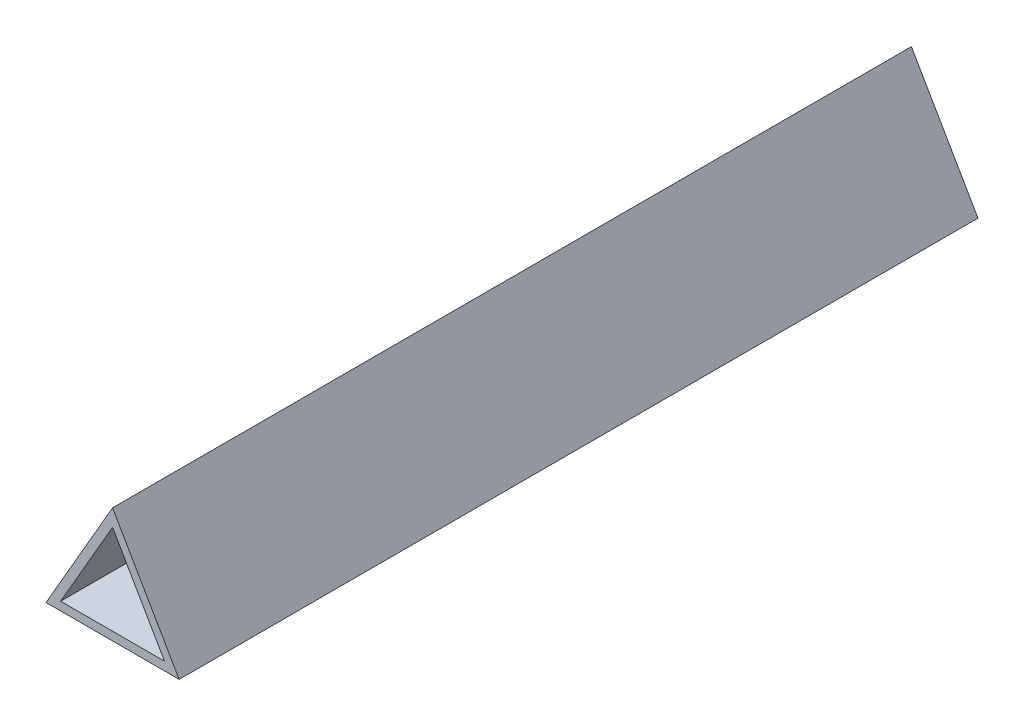
SolidWorks part; units mm, degrees
ref_plane "Front Plane" through (0, 0, 0) normal (0, 0, 1) x (1, 0, 0)
ref_plane "Top Plane" through (0, 0, 0) normal (0, 1, 0) x (1, 0, 0)
ref_plane "Right Plane" through (0, 0, 0) normal (1, 0, 0) x (0, 0, -1)
sketch "Sketch1" plane through (0, 0, 0) normal (0, 0, 1) x (1, 0, 0)
  line L0 (0, 0) -> (25, 43.3013)
  line L1 (25, 43.3013) -> (50, 0)
  line L2 (50, 0) -> (0, 0)
  line L3 (25, 36.9513) -> (5.4993, 3.175)
  line L4 (5.4993, 3.175) -> (44.5007, 3.175)
  line L5 (44.5007, 3.175) -> (25, 36.9513)
  dimension "D1" = 3.175
  dimension "D2" = 3.175
  dimension "D3" = 3.175
  dimension "D4" = 60
  dimension "D5" = 60
  dimension "D6" = 50
extrude "Boss-Extrude1" add sketch "Sketch1" along normal blind 300
